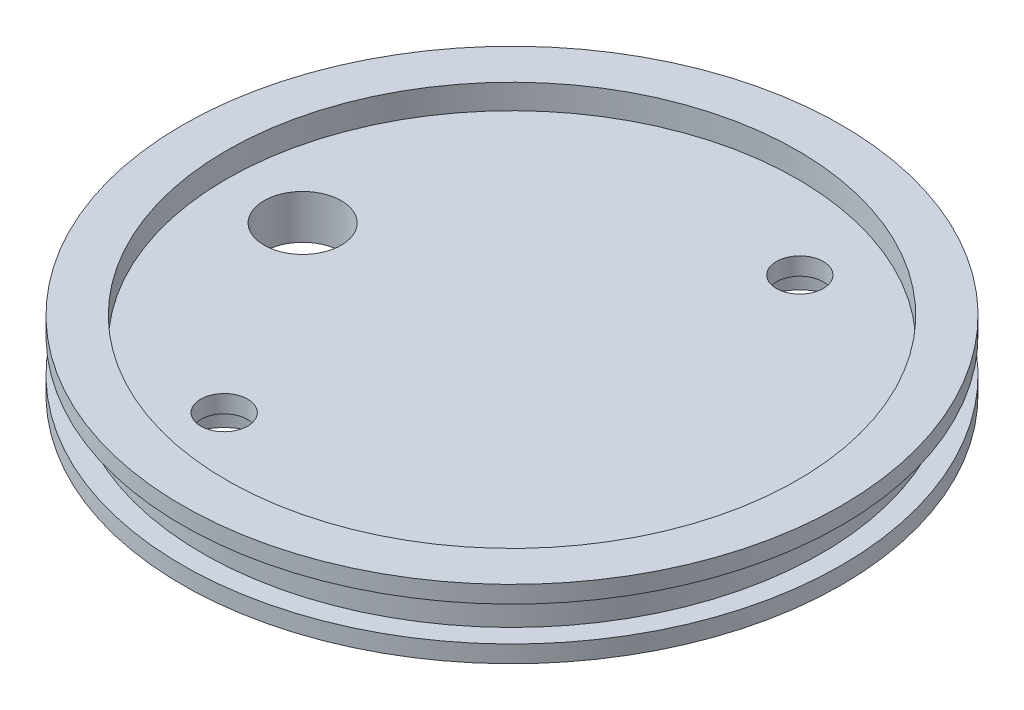
SolidWorks part; units mm, degrees
material "6061-T6 (SS)"
ref_plane "Front Plane" through (0, 0, 0) normal (0, 0, 1) x (1, 0, 0)
ref_plane "Top Plane" through (0, 0, 0) normal (0, 1, 0) x (1, 0, 0)
ref_plane "Right Plane" through (0, 0, 0) normal (1, 0, 0) x (0, 0, -1)
sketch "Sketch1" plane through (0, 0, 0) normal (0, 0, 1) x (1, 0, 0)
  line L0 (0, 48.1922) -> (0, -25.6743) construction
  line L1 (0, 0) -> (47.498, 0)
  line L2 (47.498, 0) -> (47.498, 2.4638)
  line L3 (47.498, 2.4638) -> (44.577, 2.4638)
  line L4 (44.577, 2.4638) -> (44.577, 7.4422)
  line L5 (44.577, 7.4422) -> (47.498, 7.4422)
  line L6 (47.498, 7.4422) -> (47.498, 9.906)
  line L7 (47.498, 9.906) -> (41.148, 9.906)
  line L8 (41.148, 9.906) -> (41.148, 6.35)
  line L9 (41.148, 6.35) -> (0, 6.35)
  line L10 (0, 6.35) -> (0, 0)
  dimension "D1" = 94.996
  dimension "D2" = 4.9784
  dimension "D3" = 2.921
  dimension "D4" = 9.906
  dimension "D5" = 6.35
  dimension "D6" = 6.35
revolve "Revolve1" add sketch "Sketch1" angle 360 about L0
hole_wizard "Tap Drill for 1/4 Tap - 1/4-18 NPT" positions "Sketch2" profile "Sketch3" hole size "1/4" standard "ANSI Inch" end condition through all
sketch "Sketch2" plane through (0, 6.35, 0) normal (0, 1, 0) x (1, 0, 0)
  point P3 (-30.1752, 0)
  point P10 (0, 0)
  dimension "D1" = 30.1752
sketch "Sketch3" plane through (-30.1752, 6.35, 0) normal (1, 0, 0) x (0, 0, 1)
  line L0 (0, 0) -> (0, 6.35)
  line L1 (0, 6.35) -> (5.5626, 6.35)
  line L2 (5.5626, 6.35) -> (5.5626, 0)
  line L5 (5.5626, 0) -> (0, 0)
  line L11 (0, -6.35) -> (0, 107.95) construction
  dimension "Thru Hole Dia." = 11.1252
  dimension "Thru Hole Depth" = 6.35
hole_wizard "CBORE for 1/4 Binding Head Machine Screw1" positions "Sketch4" profile "Sketch5" counterbore size "1/4" standard "ANSI Inch" end condition through all
sketch "Sketch4" plane through (0, 0, 0) normal (0, 1, 0) x (1, 0, 0)
  line L0 (0, 0) -> (-30.1752, 0)
  line L2 (0, 0) -> (12.1502, 29.3332)
  line L4 (0, 0) -> (-12.1502, -29.3332)
  point P0 (12.1502, 29.3332)
  point P2 (-12.1502, -29.3332)
  dimension "D1" = 31.75
  dimension "D2" = 112.5
sketch "Sketch5" plane through (12.1502, 0, -29.3332) normal (1, 0, 0) x (0, 0, -1)
  line L0 (0, 0) -> (0, 9.906)
  line L1 (0, 9.906) -> (3.3782, 9.906)
  line L3 (3.3782, 9.906) -> (3.3782, 3.81)
  line L4 (3.3782, 3.81) -> (6.35, 3.81)
  line L5 (6.35, 3.81) -> (6.35, 0)
  line L7 (6.35, 0) -> (0, 0)
  line L11 (0, -6.35) -> (0, 107.95) construction
  dimension "Thru Hole Dia." = 6.7564
  dimension "Thru Hole Depth" = 9.906
  dimension "C'Bore Dia." = 12.7
  dimension "C'Bore Depth" = 3.81
fillet "CNC ID Fillet" [suppressed] radius 0.1778
fillet "CNC OD Fillet" [suppressed] radius 0.127
chamfer "CNC Chamfers" [suppressed] distance 0.254 angle 45
fillet "CNC Bore Fillet" [suppressed] radius 0.254
